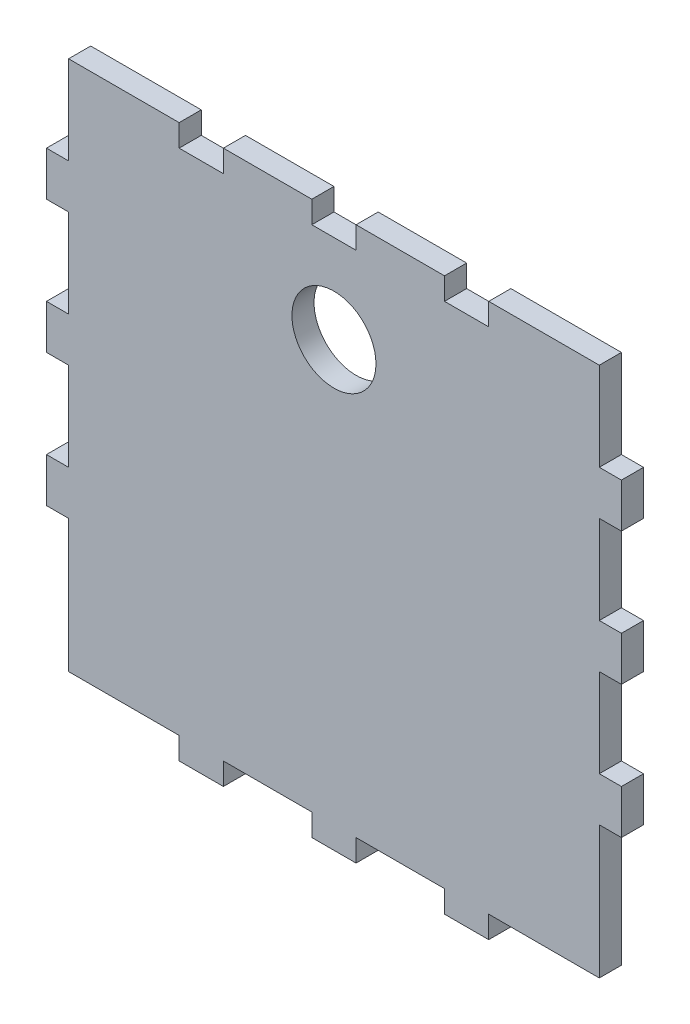
SolidWorks part; units mm, degrees
ref_plane "Ön Düzlem" through (0, 0, 0) normal (0, 0, 1) x (1, 0, 0)
ref_plane "Üst Düzlem" through (0, 0, 0) normal (0, 1, 0) x (1, 0, 0)
ref_plane "Sağ Düzlem" through (0, 0, 0) normal (1, 0, 0) x (0, 0, -1)
sketch "Sketch1" plane through (0, 0, 0) normal (0, 0, 1) x (1, 0, 0)
  line L0 (-35, 60) -> (-35, 55)
  line L1 (-60, -60) -> (-35, -60)
  line L2 (-60, -60) -> (-60, -30)
  line L3 (-60, 60) -> (-35, 60)
  line L4 (60, -60) -> (60, -30)
  line L5 (-60, -60) -> (60, 60) construction
  line L6 (-60, 60) -> (60, -60) construction
  line L7 (-35, 55) -> (-25, 55)
  line L8 (-25, 55) -> (-25, 60)
  line L9 (-35, -60) -> (-35, -65)
  line L10 (-35, -65) -> (-25, -65)
  line L11 (-25, -65) -> (-25, -60)
  line L12 (-5, -60) -> (-5, -65)
  line L13 (-5, -65) -> (5, -65)
  line L14 (5, -65) -> (5, -60)
  line L15 (-5, 55) -> (5, 55)
  line L16 (-5, 60) -> (-5, 55)
  line L17 (5, 55) -> (5, 60)
  line L18 (25, -60) -> (25, -65)
  line L19 (25, -65) -> (35, -65)
  line L20 (35, -65) -> (35, -60)
  line L21 (25, 55) -> (35, 55)
  line L22 (25, 60) -> (25, 55)
  line L23 (35, 55) -> (35, 60)
  line L24 (-60, 40) -> (-65, 40)
  line L25 (-65, 40) -> (-65, 30)
  line L26 (-65, 30) -> (-60, 30)
  line L27 (60, 40) -> (65, 40)
  line L28 (65, 40) -> (65, 30)
  line L29 (65, 30) -> (60, 30)
  line L30 (-65, 10) -> (-65, 0)
  line L31 (-60, 10) -> (-65, 10)
  line L32 (-65, 0) -> (-60, 0)
  line L33 (65, 0) -> (60, 0)
  line L34 (65, 10) -> (65, 0)
  line L35 (60, 10) -> (65, 10)
  line L36 (-65, -20) -> (-65, -30)
  line L37 (-60, -20) -> (-65, -20)
  line L38 (-65, -30) -> (-60, -30)
  line L39 (65, -30) -> (60, -30)
  line L40 (65, -20) -> (65, -30)
  line L41 (60, -20) -> (65, -20)
  line L42 (-25, 60) -> (-5, 60)
  line L43 (5, 60) -> (25, 60)
  line L44 (35, 60) -> (60, 60)
  line L45 (35, -60) -> (60, -60)
  line L46 (5, -60) -> (25, -60)
  line L47 (-25, -60) -> (-5, -60)
  line L48 (-60, -20) -> (-60, 0)
  line L49 (-60, 10) -> (-60, 30)
  line L50 (60, -20) -> (60, 0)
  line L51 (60, 10) -> (60, 30)
  line L52 (60, 40) -> (60, 60)
  line L53 (-60, 40) -> (-60, 60)
  line L54 (-65, -80) -> (-65, -90) [skipped]
  line L55 (-60, -80) -> (-65, -80) [skipped]
  line L56 (-65, -90) -> (-60, -90) [skipped]
  line L57 (65, -90) -> (60, -90) [skipped]
  line L58 (65, -80) -> (65, -90) [skipped]
  line L59 (60, -80) -> (65, -80) [skipped]
  line L60 (65, -60) -> (60, -60) [skipped]
  line L61 (65, -50) -> (65, -60) [skipped]
  line L62 (60, -50) -> (65, -50) [skipped]
  line L63 (-60, -50) -> (-65, -50) [skipped]
  line L64 (-65, -50) -> (-65, -60) [skipped]
  line L65 (-65, -60) -> (-60, -60) [skipped]
  circle A0 centre (0, 35) radius 9.5
  point P0 (0, 0)
  dimension "D13" = 19
  dimension "D1" = 120
  dimension "D2" = 25
  dimension "D3" = 5
  dimension "D4" = 10
  dimension "D6" = 20
  dimension "D7" = 5
  dimension "D8" = 10
  dimension "D9" = 20
  dimension "D11" = 20
  dimension "D12" = 120
  dimension "D14" = 25
  dimension "D15" = 5
  dimension "D5" = 3
  dimension "D10" = 5
extrude "Boss-Extrude1" add sketch "Sketch1" along normal blind 5 contours L27 L52 L44 L23 L21 L22 L43 L17 L15 L16 L42 L8 L7 L0 L3 L49 L31 L30 L32 L48 L37 L36 L38 L2 L1 L9 L10 L11 L47 L12 L13 L14 L46 L18 L19 L20 L45 L4 L39 L40 L41 L50 L33 L34 L35 L51 L29 L28
